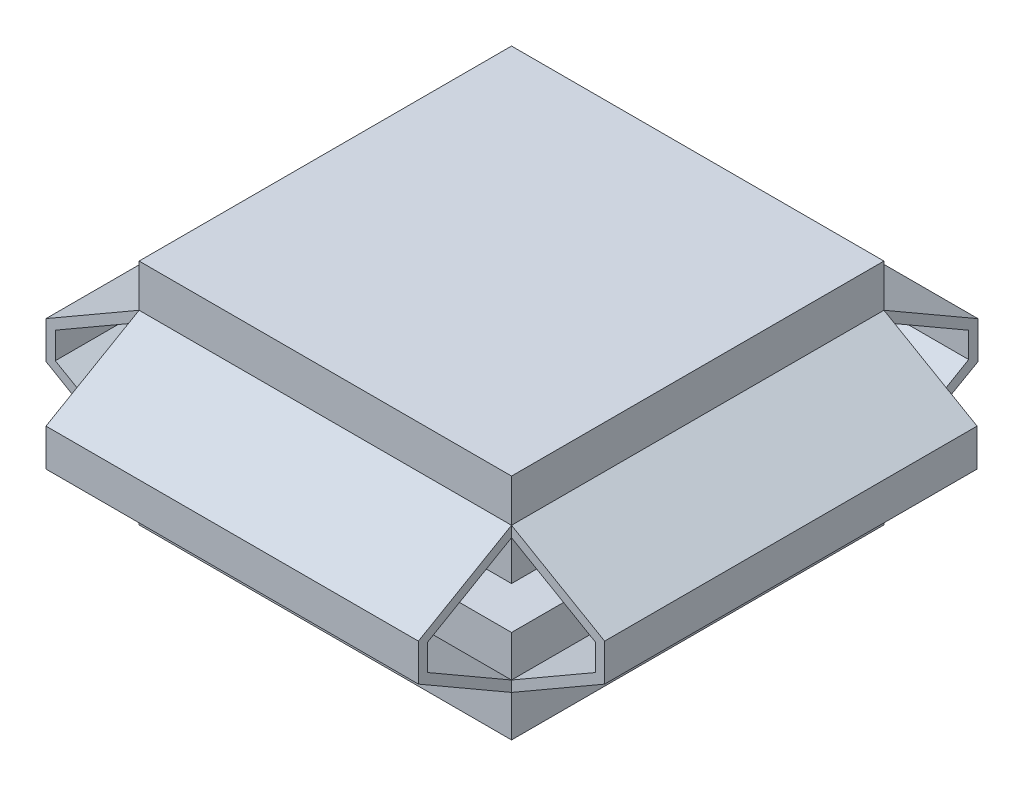
SolidWorks part; units mm, degrees
ref_plane "Front Plane" through (0, 0, 0) normal (0, 0, 1) x (1, 0, 0)
ref_plane "Top Plane" through (0, 0, 0) normal (0, 1, 0) x (1, 0, 0)
ref_plane "Right Plane" through (0, 0, 0) normal (1, 0, 0) x (0, 0, -1)
sketch "Sketch1" plane through (0, 0, 0) normal (0, 1, 0) x (1, 0, 0)
  line L1 (-10, 10) -> (10, 10)
  line L2 (-10, 10) -> (-10, -10)
  line L3 (-10, -10) -> (10, -10)
  line L4 (10, 10) -> (10, -10)
  line L5 (-10, 10) -> (10, -10) construction
  line L6 (-10, -10) -> (10, 10) construction
  point P0 (0, 0)
  dimension "D1" = 20
  dimension "D2" = 20
extrude "Boss-Extrude1" add sketch "Sketch1" along normal blind 5
sketch "Sketch2" plane through (0, 0, 10) normal (0, 0, 1) x (1, 0, 0)
  line L0 (10, 2.2113) -> (15, 5.0981)
  line L1 (10, 5) -> (10, 0) construction
  line L3 (14.5, 5.3868) -> (10, 2.7887)
  line L4 (10, 2.7887) -> (10, 2.2113)
  line L5 (14.5, 5.3868) -> (14.5, 6.8094)
  line L6 (14.5, 6.8094) -> (10, 9.4075)
  line L7 (10, 9.4075) -> (10, 9.9848)
  line L8 (10, 9.9848) -> (15, 7.0981)
  line L9 (15, 7.0981) -> (15, 5.0981)
  line L10 (10, 3.8476) -> (10, 18.1126) construction
  line L11 (14.5, 5.3868) -> (1.7747, 5.3868) construction
  line L12 (14.5, 6.8094) -> (3.8321, 6.8094) construction
  point P9 (10, 2.5)
  point P12 (10, 2.5)
  point P15 (10, 9.6962)
  dimension "D1" = 30
  dimension "D2" = 5
  dimension "D3" = 0.5
  dimension "D4" = 0.5
  dimension "D5" = 2
  dimension "D6" = 0.5
  dimension "D7" = 30
extrude "Boss-Extrude2" add sketch "Sketch2" against normal blind 20
mirror "Mirror1" about plane through (0, 0, 0) normal (1, 0, 0) of "Boss-Extrude2"
sketch "Sketch7" plane through (10, 0, 0) normal (1, 0, 0) x (0, 0, -1)
  line L0 (-10, 2.2113) -> (-10, 2.7887)
  line L1 (-10, 2.7887) -> (-14.5, 5.3868)
  line L3 (-15, 5.0981) -> (-10, 2.2113)
  line L4 (-10, 5.0981) -> (-15.5232, 5.0981) construction
  line L5 (-14.5, 5.3868) -> (-14.5, 6.8094)
  line L6 (-14.5, 6.8094) -> (-10, 9.4075)
  line L7 (-10, 7.0981) -> (-10, 9.9848) construction
  line L8 (-10, 9.4075) -> (-10, 9.9848)
  line L9 (-10, 9.9848) -> (-15, 7.0981)
  line L10 (-15, 7.0981) -> (-15, 5.0981)
  line L11 (10, 7.0981) -> (-10, 7.0981) construction
  dimension "D1" = 0.5
  dimension "D2" = 30
  dimension "D3" = 0.5
  dimension "D4" = 30
extrude "Boss-Extrude4" add sketch "Sketch7" against normal blind 20 separate body
sketch "Sketch8" plane through (10, 0, 0) normal (1, 0, 0) x (0, 0, -1)
  line L0 (10, 2.2113) -> (10, 2.7887)
  line L1 (10, 2.7887) -> (14.5506, 5.416)
  line L2 (14.5506, 5.416) -> (14.5506, 6.7802)
  line L3 (14.5506, 6.7802) -> (10, 9.4075)
  line L4 (10, 9.4075) -> (10, 9.9848)
  line L5 (10, 9.9848) -> (15.0506, 7.0688)
  line L6 (15.0506, 7.0688) -> (15.0506, 5.0688)
  line L7 (15.0506, 5.0688) -> (10, 2.2113)
  line L8 (10, 5.0981) -> (-10, 5.0981) construction
  line L9 (10, 7.0981) -> (-10, 7.0981) construction
  dimension "D1" = 0.5
  dimension "D2" = 0.5
  dimension "D3" = 0.5
  dimension "D4" = 30
  dimension "D5" = 30
  dimension "D6" = 2
extrude "Boss-Extrude6" add sketch "Sketch8" against normal blind 20 separate body
ref_plane "Plane3" through (0, 6.137, 0) normal (0, 1, 0) x (1, 0, 0)
mirror "Mirror2" about plane through (0, 6.137, 0) normal (0, 1, 0) of "Boss-Extrude1"
